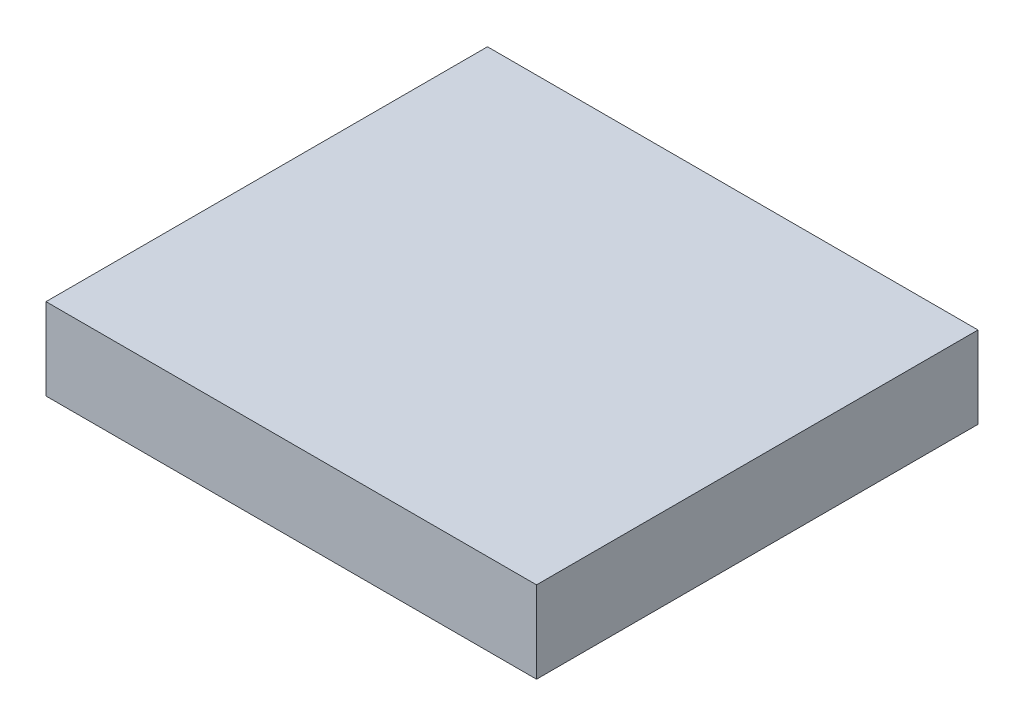
SolidWorks part; units mm, degrees
ref_plane "前视基准面" through (0, 0, 0) normal (0, 0, 1) x (1, 0, 0)
ref_plane "上视基准面" through (0, 0, 0) normal (0, 1, 0) x (1, 0, 0)
ref_plane "右视基准面" through (0, 0, 0) normal (1, 0, 0) x (0, 0, -1)
sketch "草图1" plane through (0, 0, 0) normal (0, 1, 0) x (1, 0, 0)
  line L1 (0, 0) -> (60, 0)
  line L2 (0, 0) -> (0, -54)
  line L3 (0, -54) -> (60, -54)
  line L4 (60, 0) -> (60, -54)
  dimension "D1" = 54
  dimension "D2" = 60
extrude "凸台-拉伸1" add sketch "草图1" along normal blind 10
